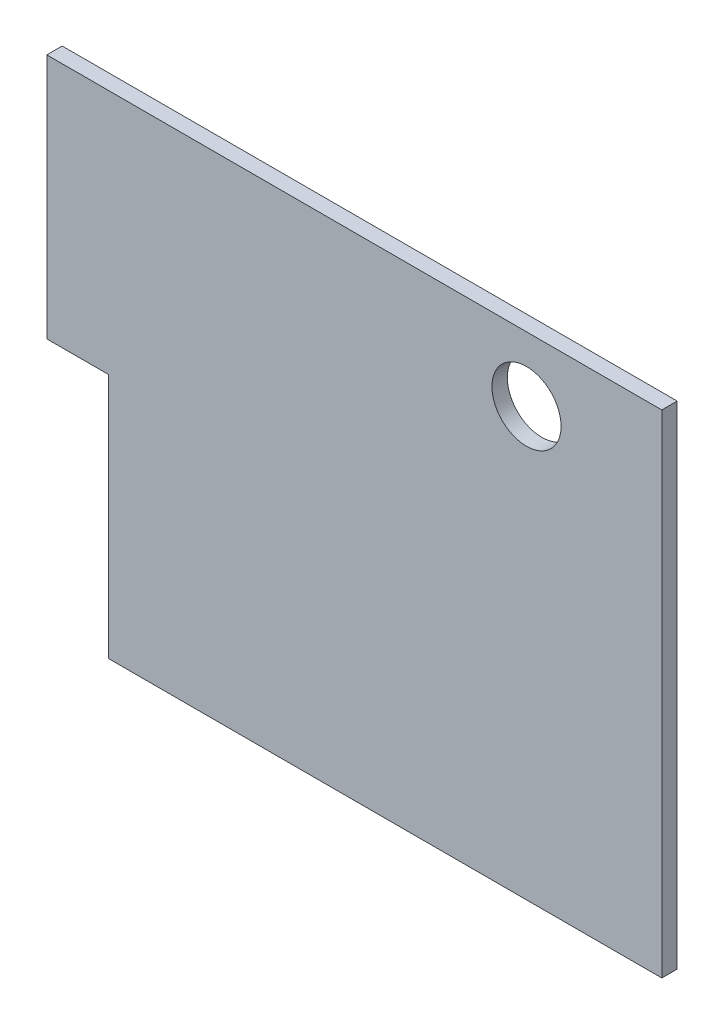
SolidWorks part; units mm, degrees
ref_plane "Front Plane" through (0, 0, 0) normal (0, 0, 1) x (1, 0, 0)
ref_plane "Top Plane" through (0, 0, 0) normal (0, 1, 0) x (1, 0, 0)
ref_plane "Right Plane" through (0, 0, 0) normal (1, 0, 0) x (0, 0, -1)
sketch "Sketch1" plane through (0, 0, 0) normal (0, 0, 1) x (1, 0, 0)
  line L1 (-127, -101.6) -> (127, -101.6)
  line L2 (-127, -101.6) -> (-127, 101.6)
  line L3 (-127, 101.6) -> (127, 101.6)
  line L4 (127, -101.6) -> (127, 101.6)
  line L5 (-127, -101.6) -> (127, 101.6) construction
  line L6 (-127, 101.6) -> (127, -101.6) construction
  point P0 (0, 0)
  dimension "D1" = 254
  dimension "D2" = 203.2
extrude "Boss-Extrude1" add sketch "Sketch1" along normal blind 6.35
sketch "Sketch2" plane through (0, 0, 6.35) normal (0, 0, 1) x (1, 0, 0)
  line L0 (127, 101.6) -> (-127, 101.6) construction
  line L1 (127, -101.6) -> (127, 101.6) construction
  line L7 (-127, -101.6) -> (-101.6, -101.6)
  line L8 (-127, -101.6) -> (-127, 0)
  line L9 (-127, 0) -> (-101.6, 0)
  line L10 (-101.6, -101.6) -> (-101.6, 0)
  circle A0 centre (71.12, 74.93) radius 14.2748
  dimension "D3" = 28.5496
  dimension "D1" = 26.67
  dimension "D2" = 55.88
  dimension "D4" = 101.6
  dimension "D5" = 25.4
extrude "Cut-Extrude1" cut sketch "Sketch2" against normal through all
